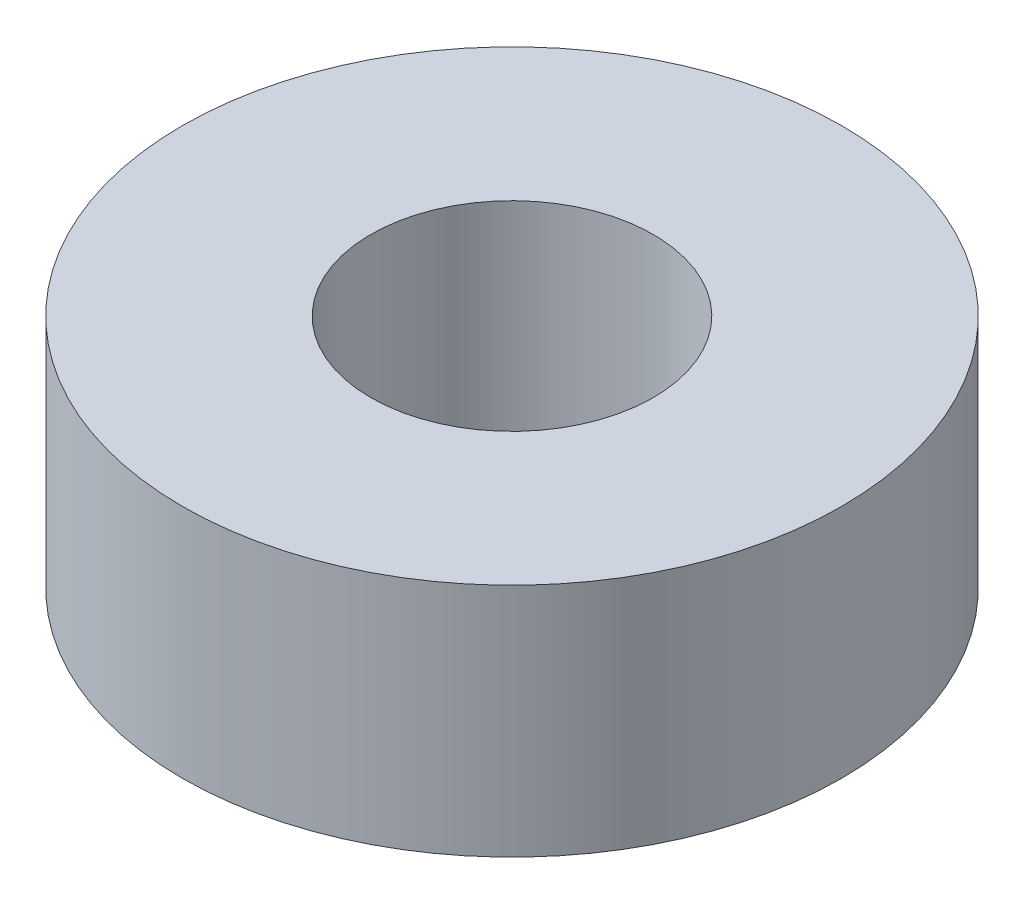
SolidWorks part; units mm, degrees
ref_plane "Front Plane" through (0, 0, 0) normal (0, 0, 1) x (1, 0, 0)
ref_plane "Top Plane" through (0, 0, 0) normal (0, 1, 0) x (1, 0, 0)
ref_plane "Right Plane" through (0, 0, 0) normal (1, 0, 0) x (0, 0, -1)
sketch "Sketch1" plane through (0, 0, 0) normal (0, 1, 0) x (1, 0, 0)
  circle A0 centre (0, 0) radius 3
  circle A1 centre (0, 0) radius 7
  dimension "D1" = 6
  dimension "D2" = 14
extrude "Boss-Extrude1" add sketch "Sketch1" along normal blind 5
